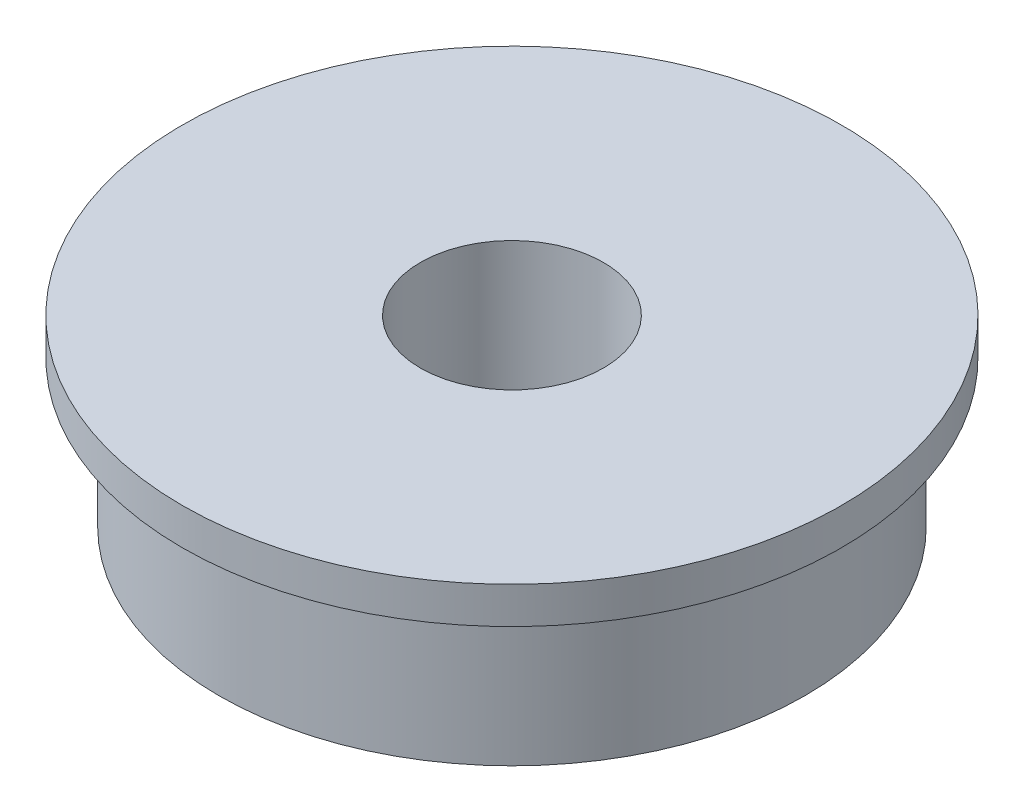
SolidWorks part; units mm, degrees
ref_plane "Front Plane" through (0, 0, 0) normal (0, 0, 1) x (1, 0, 0)
ref_plane "Top Plane" through (0, 0, 0) normal (0, 1, 0) x (1, 0, 0)
ref_plane "Right Plane" through (0, 0, 0) normal (1, 0, 0) x (0, 0, -1)
sketch "Sketch1" plane through (0, 0, 0) normal (0, 1, 0) x (1, 0, 0)
  circle A0 centre (0, 0) radius 2.5
  circle A1 centre (0, 0) radius 8
  dimension "D1" = 5
  dimension "D2" = 16
extrude "Boss-Extrude1" add sketch "Sketch1" along normal blind 4
sketch "Sketch2" plane through (0, 4, 0) normal (0, 1, 0) x (1, 0, 0)
  circle A0 centre (0, 0) radius 9
  circle A1 centre (0, 0) radius 2.5 construction
  circle A2 centre (0, 0) radius 2.5
  dimension "D1" = 18
extrude "Boss-Extrude2" add sketch "Sketch2" along normal blind 1
